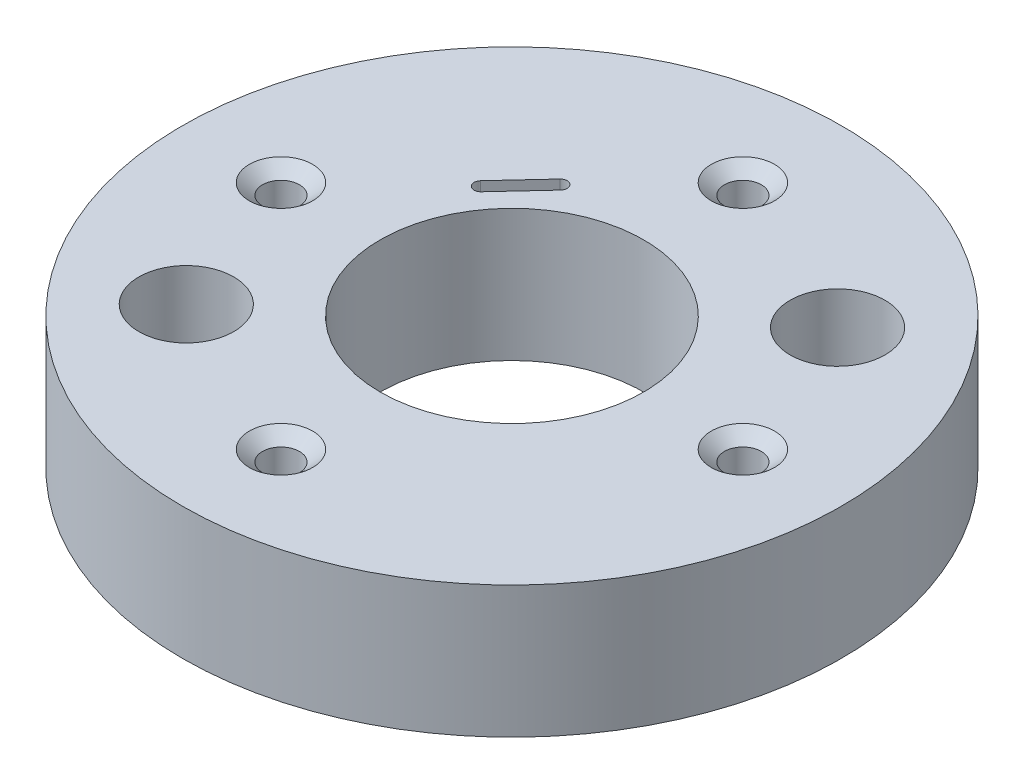
SolidWorks part; units mm, degrees
ref_plane "Front Plane" through (0, 0, 0) normal (0, 0, 1) x (1, 0, 0)
ref_plane "Top Plane" through (0, 0, 0) normal (0, 1, 0) x (1, 0, 0)
ref_plane "Right Plane" through (0, 0, 0) normal (1, 0, 0) x (0, 0, -1)
sketch "Sketch1" plane through (0, 0, 0) normal (0, 1, 0) x (1, 0, 0)
  circle A0 centre (0, 0) radius 15.875
  dimension "D1" = 31.75
extrude "Boss-Extrude1" add sketch "Sketch1" along normal blind 6.35
sketch "Sketch2" plane through (0, 6.35, 0) normal (0, 1, 0) x (1, 0, 0)
  circle A0 centre (0, 0) radius 6.35
  dimension "D1" = 12.7
extrude "Cut-Extrude1" cut sketch "Sketch2" against normal through all
sketch "Sketch5" plane through (0, 6.35, 0) normal (0, 1, 0) x (1, 0, 0)
  line L0 (0, 0) -> (0, 11.1252)
  line L1 (0, 0) -> (11.1252, 0)
  dimension "D1" = 11.1252
  dimension "D2" = 11.1252
hole_wizard "Tap Drill for #2-56 Tap2" positions "Sketch6" profile "Sketch7" hole size "#2-56" standard "ANSI Inch" end condition through all
sketch "Sketch6" plane through (0, 6.35, 0) normal (0, 1, 0) x (1, 0, 0)
  point P0 (0, 11.1252)
sketch "Sketch7" plane through (0, 6.35, -11.1252) normal (1, 0, 0) x (0, 0, 1)
  line L0 (0, 0) -> (0, 6.35)
  line L1 (0, 6.35) -> (0.889, 6.35)
  line L2 (0.889, 6.35) -> (0.889, 0.5328)
  line L3 (0.889, 0.5328) -> (1.524, 0)
  line L5 (1.524, 0) -> (0, 0)
  line L6 (-0.889, 0.5328) -> (-1.524, 0) construction
  line L11 (0, -6.35) -> (0, 107.95) construction
  dimension "Thru Hole Dia." = 1.778
  dimension "Thru Hole Depth" = 6.35
  dimension "Near C'Sink Dia." = 3.048
  dimension "Near C'Sink Angle" = 100
pattern_circular "CirPattern1" count 2 every 180 about axis through (0, 0, 0) along (0, 1, 0) of "Tap Drill for #2-56 Tap2"
hole_wizard "Tap Drill for #2-56 Tap1" positions "Sketch9" profile "Sketch10" hole size "#2-56" standard "ANSI Inch"
sketch "Sketch9" plane through (0, 6.35, 0) normal (0, 1, 0) x (1, 0, 0)
  point P0 (11.1252, 0)
sketch "Sketch10" plane through (11.1252, 6.35, 0) normal (1, 0, 0) x (0, 0, 1)
  line L0 (0, 0) -> (0, 4.3442)
  line L1 (0, 4.3442) -> (0.889, 3.81)
  line L2 (0.889, 3.81) -> (0.889, 0.5328)
  line L3 (0.889, 0.5328) -> (1.524, 0)
  line L5 (1.524, 0) -> (0, 0)
  line L6 (-0.889, 0.5328) -> (-1.524, 0) construction
  line L10 (0, 4.3442) -> (-0.889, 3.81) construction
  line L11 (0, -6.35) -> (0, 107.95) construction
  dimension "Hole Dia." = 1.778
  dimension "Hole Depth" = 3.81
  dimension "Near C'Sink Dia." = 3.048
  dimension "Near C'Sink Angle" = 100
  dimension "Drill Angle" = 118
pattern_circular "CirPattern2" count 2 over 360 about axis through (0, 0, 0) along (0, 1, 0) of "Tap Drill for #2-56 Tap1"
sketch "Sketch11" plane through (0, 6.35, 0) normal (0, 1, 0) x (1, 0, 0)
  line L0 (0, 0) -> (8.3289, 7.3564)
  circle A0 centre (8.3289, 7.3564) radius 2.286
  dimension "D2" = 4.572
  dimension "D1" = 11.1125
extrude "Cut-Extrude2" cut sketch "Sketch11" against normal through all contours A0
pattern_circular "CirPattern3" count 2 every 180 about axis through (0, 0, 0) along (0, 1, 0) of "Cut-Extrude2"
sketch "Sketch12" plane through (0, 6.35, 0) normal (0, 1, 0) x (1, 0, 0)
  line L0 (-4.3143, 6.6475) -> (-6.1577, 4.6609)
  line L1 (-4.3143, 6.6475) -> (-5.236, 5.6542)
  line L2 (-6.1577, 4.6609) -> (-4.3143, 6.6475) construction
  line L7 (-6.3976, 4.8835) -> (-4.5542, 6.8701)
  line L8 (-5.9178, 4.4383) -> (-4.0744, 6.4249)
  arc A0 (-6.3976, 4.8835) -> (-5.9178, 4.4383) centre (-6.1577, 4.6609) ccw
  arc A1 (-4.0744, 6.4249) -> (-4.5542, 6.8701) centre (-4.3143, 6.6475) ccw
  point P4 (-5.236, 5.6542)
extrude "Cut-Extrude3" cut sketch "Sketch12" against normal through all contours A0 L8 A1 L7
